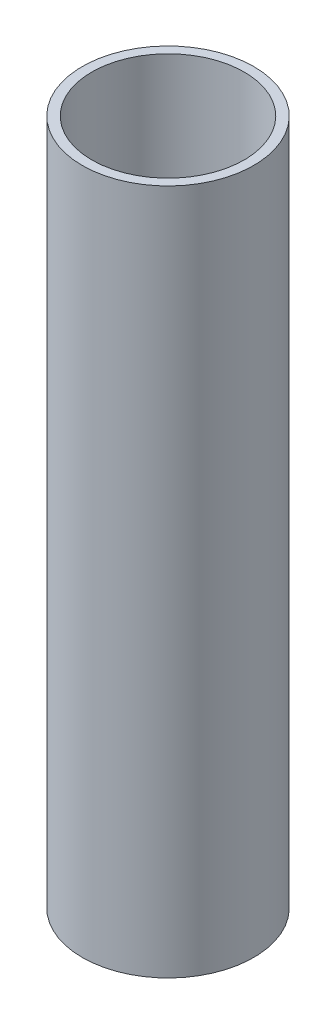
SolidWorks part; units mm, degrees
ref_plane "Front Plane" through (0, 0, 0) normal (0, 0, 1) x (1, 0, 0)
ref_plane "Top Plane" through (0, 0, 0) normal (0, 1, 0) x (1, 0, 0)
ref_plane "Right Plane" through (0, 0, 0) normal (1, 0, 0) x (0, 0, -1)
sketch "Sketch1" plane through (0, 0, 0) normal (0, 1, 0) x (1, 0, 0)
  circle A0 centre (0, 0) radius 50.8
  circle A1 centre (0, 0) radius 57.15
  dimension "D1" = 101.6
  dimension "D2" = 114.3
extrude "Boss-Extrude1" add sketch "Sketch1" along normal mid plane 457.2
